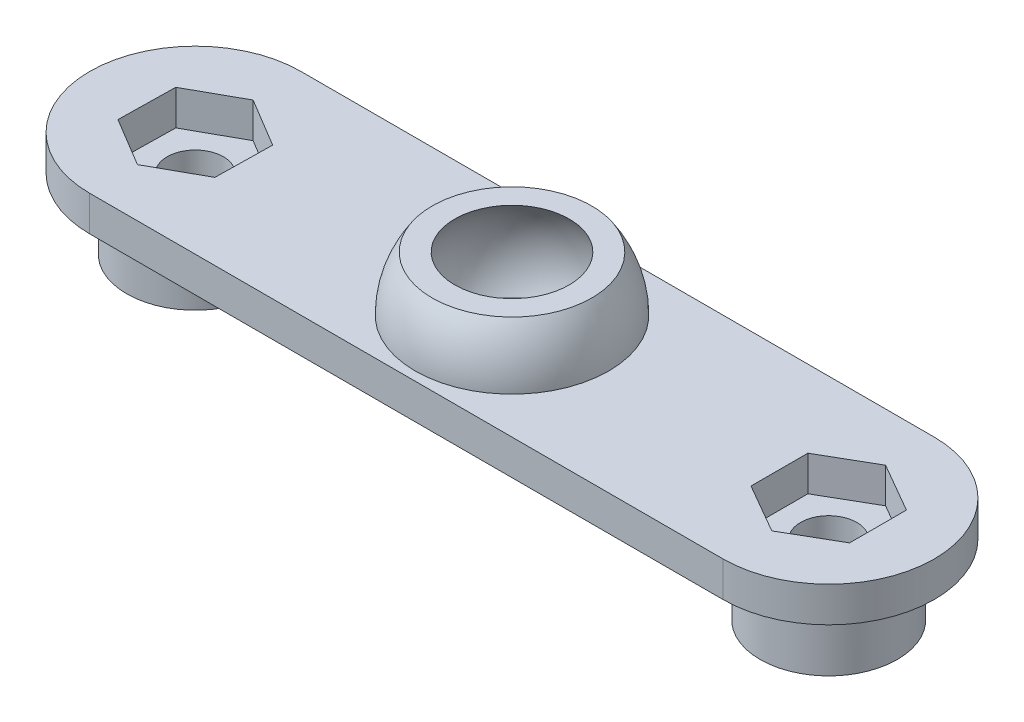
SolidWorks part; units mm, degrees
ref_plane "Front Plane" through (0, 0, 0) normal (0, 0, 1) x (1, 0, 0)
ref_plane "Top Plane" through (0, 0, 0) normal (0, 1, 0) x (1, 0, 0)
ref_plane "Right Plane" through (0, 0, 0) normal (1, 0, 0) x (0, 0, -1)
sketch "Sketch1" plane through (0, 0, 0) normal (0, 1, 0) x (1, 0, 0)
  line L0 (-22.4891, 0) -> (22.0986, 0) construction
  line L1 (0, 9.3089) -> (0, -7.5188) construction
  line L2 (-18, 0) -> (18, 0) construction
  line L3 (-18, 6) -> (18, 6)
  line L4 (-18, -6) -> (18, -6)
  circle A0 centre (18, 0) radius 1.6
  circle A1 centre (-18, 0) radius 1.6
  arc A2 (-18, 6) -> (-18, -6) centre (-18, 0) ccw
  arc A3 (18, -6) -> (18, 6) centre (18, 0) ccw
  circle A4 centre (0, 0) radius 4.5
  point P9 (0, 0)
  dimension "D1" = 3.2
  dimension "D3" = 6
  dimension "D4" = 9
  dimension "D2" = 18
extrude "Boss-Extrude1" add sketch "Sketch1" along normal blind 2
sketch "Sketch2" plane through (0, 0, 0) normal (0, -1, 0) x (1, 0, 0)
  circle A0 centre (-18, 0) radius 1.6
  circle A1 centre (18, 0) radius 1.6
  circle A2 centre (-18, 0) radius 3.9
  circle A3 centre (18, 0) radius 3.9
  circle A4 centre (18, 0) radius 1.6 construction
  circle A5 centre (-18, 0) radius 1.6 construction
  dimension "D1" = 7.8
extrude "Boss-Extrude2" add sketch "Sketch2" along normal blind 4
sketch "Sketch3" plane through (0, 0, 0) normal (1, 0, 0) x (0, 0, -1)
  line L0 (0, 5.8003) -> (0, -6.7244) construction
  line L1 (-7.4626, 2) -> (9.0003, 2) construction
  line L2 (6, 2) -> (-6, 2) construction
  line L3 (-7.4626, 0) -> (9.0003, 0) construction
  line L4 (-3.25, 5.1125) -> (3.25, 5.1125) construction
  line L5 (-3.25, 5.1125) -> (-4.5346, 5.1125)
  line L6 (3.25, 5.1125) -> (4.5346, 5.1125)
  line L7 (-4.0311, 0) -> (-5.1235, 0)
  line L8 (4.0311, 0) -> (5.1235, 0)
  arc A0 (5.1235, 0) -> (4.5346, 5.1125) centre (0, 2) ccw
  arc A1 (4.0311, 0) -> (3.25, 5.1125) centre (0, 2) ccw
  arc A2 (-4.5346, 5.1125) -> (-5.1235, 0) centre (0, 2) ccw
  arc A3 (-3.25, 5.1125) -> (-4.0311, 0) centre (0, 2) ccw
  dimension "D1" = 9
  dimension "D2" = 11
  dimension "D3" = 6.5
revolve "Revolve1" add sketch "Sketch3" angle 360 about L0
sketch "Sketch4" plane through (0, 2, 0) normal (0, 1, 0) x (1, 0, 0)
  line L1 (-15.2271, -1.6627) -> (-15.1737, 1.5701)
  line L2 (-15.1737, 1.5701) -> (-17.9465, 3.2327)
  line L3 (-17.9465, 3.2327) -> (-20.7729, 1.6627)
  line L4 (-20.7729, 1.6627) -> (-20.8263, -1.5701)
  line L5 (-20.8263, -1.5701) -> (-18.0535, -3.2327)
  line L6 (-18.0535, -3.2327) -> (-15.2271, -1.6627)
  line L7 (18, -3.2332) -> (20.8, -1.6166)
  line L8 (20.8, -1.6166) -> (20.8, 1.6166)
  line L9 (20.8, 1.6166) -> (18, 3.2332)
  line L10 (18, 3.2332) -> (15.2, 1.6166)
  line L11 (15.2, 1.6166) -> (15.2, -1.6166)
  line L12 (15.2, -1.6166) -> (18, -3.2332)
  circle A0 centre (-18, 0) radius 2.8 construction
  circle A1 centre (18, 0) radius 2.8 construction
  dimension "D1" = 5.6
  dimension "D2" = 5.6
extrude "Cut-Extrude1" cut sketch "Sketch4" against normal blind 2
